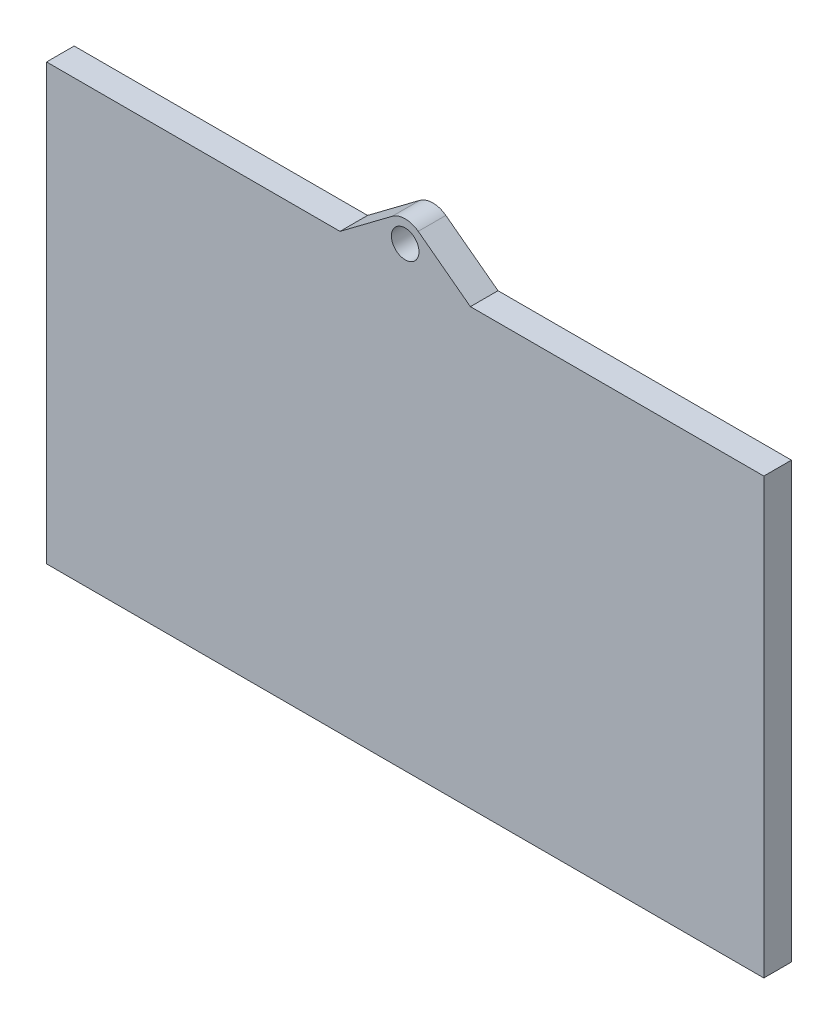
SolidWorks part; units mm, degrees
ref_plane "Front Plane" through (0, 0, 0) normal (0, 0, 1) x (1, 0, 0)
ref_plane "Top Plane" through (0, 0, 0) normal (0, 1, 0) x (1, 0, 0)
ref_plane "Right Plane" through (0, 0, 0) normal (1, 0, 0) x (0, 0, -1)
sketch "Sketch1" plane through (0, 0, 0) normal (0, 0, 1) x (1, 0, 0)
  line L1 (-82.5, 50) -> (82.5, 50)
  line L2 (-82.5, 50) -> (-82.5, -50)
  line L3 (-82.5, -50) -> (82.5, -50)
  line L4 (82.5, 50) -> (82.5, -50)
  line L5 (-82.5, 50) -> (82.5, -50) construction
  line L6 (-82.5, -50) -> (82.5, 50) construction
  point P0 (0, 0)
  dimension "D1" = 165
  dimension "D2" = 100
extrude "Boss-Extrude1" add sketch "Sketch1" along normal blind 6.35
sketch "Sketch2" plane through (0, 0, 6.35) normal (0, 0, 1) x (1, 0, 0)
  line L0 (82.5, 50) -> (-82.5, 50) construction
  line L1 (-3, 59) -> (-15, 50)
  line L2 (3, 59) -> (15, 50)
  line L3 (0, 55) -> (0, 50) construction
  line L4 (-15, 50) -> (15, 50)
  circle A0 centre (0, 55) radius 3.175
  arc A1 (3, 59) -> (-3, 59) centre (0, 55) ccw
  dimension "D1" = 6.35
  dimension "D2" = 5
  dimension "D3" = 30
extrude "Boss-Extrude2" add sketch "Sketch2" against normal up to surface (6.35 mm away) up to face at (0, 0, 0)
